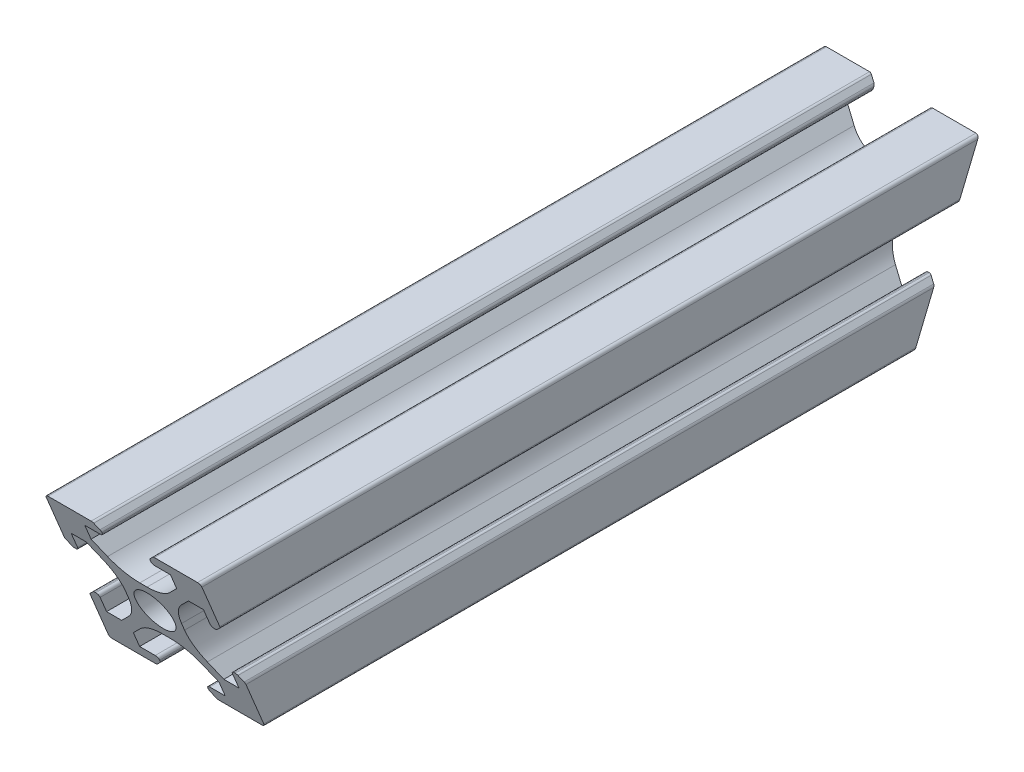
SolidWorks part; units mm, degrees
material "6063-T83"
ref_plane "Plano frontal" through (0, 0, 0) normal (0, 0, 1) x (1, 0, 0)
ref_plane "Plano superior" through (0, 0, 0) normal (0, 1, 0) x (1, 0, 0)
ref_plane "Plano direito" through (0, 0, 0) normal (1, 0, 0) x (0, 0, -1)
sketch "Esboço1" plane through (0, 0, 0) normal (0, 0, 1) x (1, 0, 0)
  line L0 (-9.0343, 3.1) -> (-8.9, 3.1)
  line L3 (-10, 10) -> (-4.0657, 10)
  line L5 (-10, -10) -> (10, 10) construction
  line L6 (-10, 10) -> (10, -10) construction
  line L7 (-8.5, 3.5) -> (-8.5, 5.5)
  line L8 (-10, 0) -> (10, 0) construction
  line L9 (0, 10) -> (0, -10) construction
  line L12 (-8.5, 5.5) -> (-6.5607, 5.5)
  line L15 (-6.5607, 5.5) -> (-5.0645, 4.0038)
  line L16 (-3.6, 0.4683) -> (-3.6, 0)
  line L17 (-0.4683, 3.6) -> (0, 3.6)
  line L18 (-5.5, 6.5607) -> (-4.0038, 5.0645)
  line L21 (-5.5, 8.5) -> (-5.5, 6.5607)
  line L24 (-3.5, 8.5) -> (-5.5, 8.5)
  line L25 (-3.1, 9.0343) -> (-3.1, 8.9)
  line L44 (-10, 4.0657) -> (-10, 10)
  line L45 (-9.8828, 3.7828) -> (-9.3172, 3.2172)
  line L46 (-3.7828, 9.8828) -> (-3.2172, 9.3172)
  line L47 (-3.6, 0) -> (-2.5, 0)
  line L48 (0, 3.6) -> (0, 2.5)
  arc A0 (-3.5, 8.5) -> (-3.1, 8.9) centre (-3.5, 8.9) ccw
  arc A1 (-3.7828, 9.8828) -> (-4.0657, 10) centre (-4.0657, 9.6) ccw
  arc A2 (-10, 4.0657) -> (-9.8828, 3.7828) centre (-9.6, 4.0657) ccw
  arc A3 (-8.5, 3.5) -> (-8.9, 3.1) centre (-8.9, 3.5) cw
  arc A4 (-3.2172, 9.3172) -> (-3.1, 9.0343) centre (-3.5, 9.0343) cw
  arc A5 (-9.3172, 3.2172) -> (-9.0343, 3.1) centre (-9.0343, 3.5) ccw
  arc A6 (-3.6, 0.4683) -> (-5.0645, 4.0038) centre (-8.6, 0.4683) ccw
  arc A7 (-4.0038, 5.0645) -> (-0.4683, 3.6) centre (-0.4683, 8.6) ccw
  circle A8 centre (0, 0) radius 2.5
  point P6 (-10, 3.1)
  point P28 (-3.1, 8.5)
  point P31 (-3.1, 10)
  point P33 (-3.9, 10)
  point P36 (-10, 3.9)
  point P39 (-8.5, 3.1)
  point P42 (-3.1, 9.2)
  point P45 (-9.2, 3.1)
  point P48 (-3.6, 2.5393)
  point P51 (-2.5393, 3.6)
  dimension "D5" = 10
  dimension "D9" = 0.4
  dimension "D10" = 0.4
  dimension "D11" = 5
  dimension "D12" = 5
  dimension "D13" = 5
  dimension "D1" = 6.9
  dimension "D2" = 1.5
  dimension "D3" = 3.6
  dimension "D4" = 1.5
  dimension "D6" = 2.4
  dimension "D7" = 3.6
  dimension "D8" = 45
extrude "Ressalto-extrusão1" add sketch "Esboço1" along normal blind 100
sketch "Esboço3" plane through (0, 0, 0) normal (1, 0, 0) x (0, 0, -1)
  line L0 (0, 0) -> (-100, 0) construction
  line L1 (-100, 2.5) -> (-100, 0) construction
  point P3 (-86.3596, 0)
  point P4 (0, 0)
pattern_circular "PadrãoCircular1" count 4 every 90 about axis through (0, 0, 0) along (0, 0, 1) of "Ressalto-extrusão1"
fillet "Filete1" radius 0.4 4 edges at (-10, -10, 50) (-10, 10, 50) (10, -10, 50) (10, 10, 50)
ref_plane "Plane1" through (0, 0, 50) normal (0, 0, 1) x (1, 0, 0)
sketch "Sketch1" plane through (-10, 0, 0) normal (-1, 0, 0) x (0, 0, 1)
  line L0 (0, 10) -> (0, -10)
  line L1 (0, 0) -> (100, 0) construction
  line L2 (0, 10) -> (8.2843, -10)
  line L3 (0, -10) -> (8.2843, -10)
  line L4 (50, 9.6) -> (50, -9.6) construction
  line L5 (100, 9.6) -> (0, 9.6) construction
  line L6 (0, -9.6) -> (100, -9.6) construction
  line L7 (100, 9.6) -> (100, -9.6)
  line L8 (100, -10) -> (91.7157, -10)
  line L9 (100, 10) -> (91.7157, -10)
  line L10 (100, 10) -> (100, -10)
  line M5 (100, 4.0657) -> (100, 9.6)
  line M6 (100, 9.6) -> (0, 9.6)
  line M7 (0, 9.6) -> (0, 4.0657)
  line M8 (0, 4.0657) -> (100, 4.0657)
  dimension "D1" = 10
  dimension "D2" = 22.5
extrude "Cut-Extrude1" cut sketch "Sketch1" against normal through all contours L0 L3 L2 M8 | L2 M6 M7 M8 | L9 M6 M8 M5 | L10 L7 L9 L8 M8 | L10 L9 M6 | L2 L0 M6
